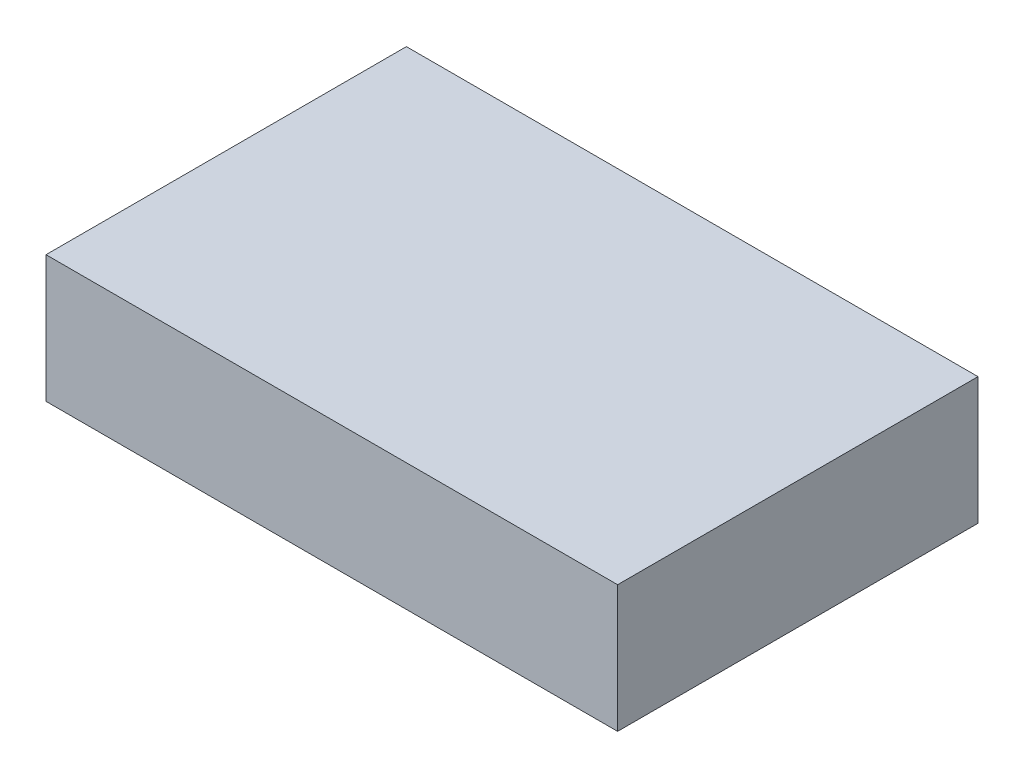
SolidWorks part; units mm, degrees
ref_plane "Front Plane" through (0, 0, 0) normal (0, 0, 1) x (1, 0, 0)
ref_plane "Top Plane" through (0, 0, 0) normal (0, 1, 0) x (1, 0, 0)
ref_plane "Right Plane" through (0, 0, 0) normal (1, 0, 0) x (0, 0, -1)
sketch "Sketch1" plane through (0, 0, 0) normal (0, 1, 0) x (1, 0, 0)
  line L1 (-26.025, -15.3) -> (26.025, -15.3)
  line L2 (-26.025, -15.3) -> (-26.025, 15.3)
  line L3 (-26.025, 15.3) -> (26.025, 15.3)
  line L4 (26.025, -15.3) -> (26.025, 15.3)
  line L5 (-26.025, -15.3) -> (26.025, 15.3) construction
  line L6 (-26.025, 15.3) -> (26.025, -15.3) construction
  line L7 (-27.025, -16.3) -> (27.025, -16.3)
  line L8 (-27.025, -16.3) -> (-27.025, 16.3)
  line L9 (-27.025, 16.3) -> (27.025, 16.3)
  line L10 (27.025, -16.3) -> (27.025, 16.3)
  line L11 (-27.025, -16.3) -> (27.025, 16.3) construction
  line L12 (-27.025, 16.3) -> (27.025, -16.3) construction
  line L14 (29.025, -18.3) -> (-29.025, -18.3)
  line L15 (29.025, -18.3) -> (29.025, 18.3)
  line L16 (29.025, 18.3) -> (-29.025, 18.3)
  line L17 (-29.025, -18.3) -> (-29.025, 18.3)
  line L18 (29.025, -18.3) -> (-29.025, 18.3) construction
  line L19 (29.025, 18.3) -> (-29.025, -18.3) construction
  point P0 (0, 0)
  point P6 (0, 0)
  point P12 (0, 0)
  dimension "D5" = 2
  dimension "D1" = 30.6
  dimension "D2" = 52.05
  dimension "D3" = 1
  dimension "D4" = 1
  dimension "D6" = 2
extrude "Boss-Extrude2" add sketch "Sketch1" along normal blind 12.9 contours L17 L16 L15 L14
sketch "Sketch4" plane through (0, 12.9, 0) normal (0, 1, 0) x (1, 0, 0)
  line L4 (-27.025, -16.3) -> (27.025, -16.3)
  line L5 (27.025, -16.3) -> (27.025, 16.3)
  line L6 (27.025, 16.3) -> (-27.025, 16.3)
  line L7 (-27.025, 16.3) -> (-27.025, -16.3)
  line L8 (-27.025, -16.3) -> (27.025, -16.3)
  line L9 (27.025, -16.3) -> (27.025, 16.3)
  line L10 (27.025, 16.3) -> (-27.025, 16.3)
  line L11 (-27.025, 16.3) -> (-27.025, -16.3)
  line L12 (-26.025, -15.3) -> (26.025, -15.3)
  line L13 (26.025, -15.3) -> (26.025, 15.3)
  line L14 (26.025, 15.3) -> (-26.025, 15.3)
  line L15 (-26.025, 15.3) -> (-26.025, -15.3)
  line L16 (-26.025, -15.3) -> (26.025, -15.3)
  line L17 (26.025, -15.3) -> (26.025, 15.3)
  line L18 (26.025, 15.3) -> (-26.025, 15.3)
  line L19 (-26.025, 15.3) -> (-26.025, -15.3)
  line L20 (-29.025, -18.3) -> (29.025, -18.3)
  line L21 (29.025, -18.3) -> (29.025, 18.3)
  line L22 (29.025, 18.3) -> (-29.025, 18.3)
  line L23 (-29.025, 18.3) -> (-29.025, -18.3)
  line L24 (-29.025, -18.3) -> (29.025, -18.3)
  line L25 (29.025, -18.3) -> (29.025, 18.3)
  line L26 (29.025, 18.3) -> (-29.025, 18.3)
  line L27 (-29.025, 18.3) -> (-29.025, -18.3)
  dimension "D1" = 0
  dimension "D2" = 0
  dimension "D3" = 0
ref_plane "Plane1" through (0, 10.3, 0) normal (0, 1, 0) x (1, 0, 0)
sketch "Sketch2" plane through (0, 10.3, 0) normal (0, 1, 0) x (1, 0, 0)
  line L0 (29.025, -18.3) -> (29.025, 18.3) construction
  line L1 (29.025, -18.3) -> (-29.025, -18.3) construction
  line L2 (-29.025, -18.3) -> (-29.025, 18.3) construction
  line L3 (29.025, 18.3) -> (-29.025, 18.3) construction
  line L4 (29.025, -18.3) -> (29.025, 18.3)
  line L5 (29.025, -18.3) -> (-29.025, -18.3)
  line L6 (-29.025, -18.3) -> (-29.025, 18.3)
  line L7 (29.025, 18.3) -> (-29.025, 18.3)
  line L8 (-27.025, -16.3) -> (27.025, -16.3) construction
  line L9 (27.025, -16.3) -> (27.025, 16.3) construction
  line L10 (-27.025, 16.3) -> (27.025, 16.3) construction
  line L11 (-27.025, -16.3) -> (-27.025, 16.3) construction
  line L12 (-27.025, -16.3) -> (27.025, -16.3)
  line L13 (27.025, -16.3) -> (27.025, 16.3)
  line L14 (-27.025, 16.3) -> (27.025, 16.3)
  line L15 (-27.025, -16.3) -> (-27.025, 16.3)
